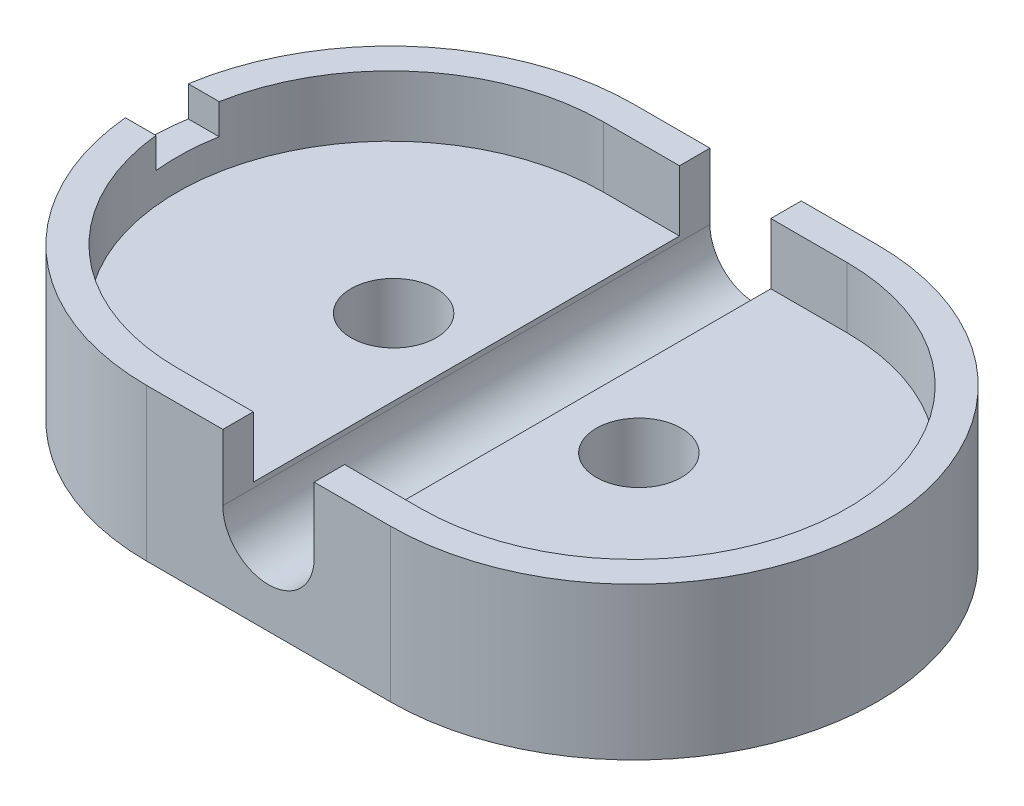
SolidWorks part; units mm, degrees
ref_plane "Plano frontal" through (0, 0, 0) normal (0, 0, 1) x (1, 0, 0)
ref_plane "Plano superior" through (0, 0, 0) normal (0, 1, 0) x (1, 0, 0)
ref_plane "Plano direito" through (0, 0, 0) normal (1, 0, 0) x (0, 0, -1)
sketch "Esboço1" plane through (0, 0, 0) normal (0, 1, 0) x (1, 0, 0)
  line L0 (0, 0) -> (40, 0)
  line L1 (40, 80) -> (0, 80)
  arc A0 (40, 0) -> (40, 80) centre (40, 40) ccw
  arc A1 (0, 80) -> (0, 0) centre (0, 40) ccw
  dimension "D1" = 40
  dimension "D2" = 40
extrude "Ressalto-extrusão1" add sketch "Esboço1" along normal blind 25
sketch "Esboço5" plane through (0, 0, 0) normal (0, 0, 1) x (1, 0, 0)
  line L0 (12.5, 25) -> (12.5, 14.1546)
  line L1 (0, 25) -> (40, 25) construction
  line L2 (27.5, 14.1546) -> (27.5, 25)
  line L3 (27.5, 25) -> (12.5, 25)
  arc A0 (12.5, 14.1546) -> (27.5, 14.1546) centre (20, 14.1546) ccw
  dimension "D1" = 15
  dimension "D2" = 12.5
extrude "Corte-extrusão1" cut sketch "Esboço5" against normal through all
sketch "Esboço6" plane through (0, 25, 0) normal (0, 1, 0) x (1, 0, 0)
  line L0 (12.5, 75) -> (0, 75)
  line L1 (12.5, 80) -> (12.5, 0) construction
  line L2 (0, 5) -> (12.5, 5)
  line L3 (12.5, 5) -> (12.5, 75)
  line L4 (12.5, 80) -> (0, 80) construction
  line L5 (0, 0) -> (12.5, 0) construction
  arc A0 (0, 75) -> (0, 5) centre (0, 40) ccw
  point P11 (6.25, 0)
  dimension "D1" = 5
  dimension "D2" = 5
extrude "Corte-extrusão2" cut sketch "Esboço6" against normal blind 10
sketch "Esboço7" plane through (0, 25, 0) normal (0, 1, 0) x (1, 0, 0)
  line L0 (27.5, 75) -> (40, 75)
  line L1 (27.5, 80) -> (27.5, 0) construction
  line L2 (40, 5) -> (27.5, 5)
  line L3 (27.5, 5) -> (27.5, 75)
  line L4 (40, 80) -> (27.5, 80) construction
  line L5 (27.5, 0) -> (40, 0) construction
  arc A0 (40, 75) -> (40, 5) centre (40, 40) cw
  dimension "D1" = 5
  dimension "D2" = 5
extrude "Corte-extrusão3" cut sketch "Esboço7" against normal blind 10
sketch "Esboço8" plane through (12.5, 0, 0) normal (1, 0, 0) x (0, 0, -1)
  line L0 (46.3231, 25) -> (46.3231, 20)
  line L1 (80, 25) -> (0, 25) construction
  line L2 (46.3231, 20) -> (36.3231, 20)
  line L3 (36.3231, 20) -> (36.3231, 25)
  line L4 (36.3231, 25) -> (46.3231, 25)
  dimension "D1" = 10
  dimension "D2" = 5
extrude "Corte-extrusão4" cut sketch "Esboço8" against normal through all
sketch "Esboço10" plane through (0, 15, 0) normal (0, 1, 0) x (1, 0, 0)
  line L0 (12.5, 5) -> (12.5, 75) construction
  circle A0 centre (0, 40.5515) radius 7
  dimension "D1" = 14
  dimension "D2" = 12.5
extrude "Corte-extrusão5" cut sketch "Esboço10" against normal through all
sketch "Esboço11" plane through (0, 15, 0) normal (0, 1, 0) x (1, 0, 0)
  line L0 (27.5, 80) -> (27.5, 0) construction
  circle A0 centre (40, 40.8273) radius 7
  dimension "D1" = 14
  dimension "D2" = 12.5
extrude "Corte-extrusão6" cut sketch "Esboço11" against normal through all
